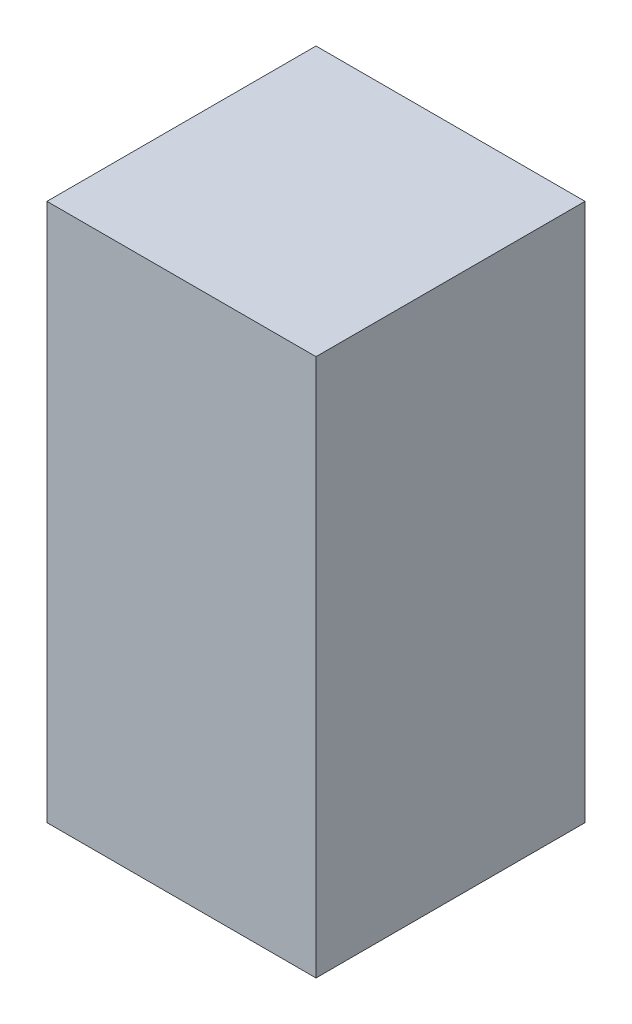
SolidWorks part; units mm, degrees
ref_plane "Front Plane" through (0, 0, 0) normal (0, 0, 1) x (1, 0, 0)
ref_plane "Top Plane" through (0, 0, 0) normal (0, 1, 0) x (1, 0, 0)
ref_plane "Right Plane" through (0, 0, 0) normal (1, 0, 0) x (0, 0, -1)
sketch "Sketch1" plane through (0, 0, 0) normal (0, 1, 0) x (1, 0, 0)
  line L1 (-150, -150) -> (150, -150)
  line L2 (-150, -150) -> (-150, 150)
  line L3 (-150, 150) -> (150, 150)
  line L4 (150, -150) -> (150, 150)
  line L5 (-150, -150) -> (150, 150) construction
  line L6 (-150, 150) -> (150, -150) construction
  point P0 (0, 0)
  dimension "D1" = 300
  dimension "D2" = 300
extrude "Boss-Extrude1" add sketch "Sketch1" along normal blind 600
sketch "Sketch2" plane through (0, 0, 0) normal (0, -1, 0) x (1, 0, 0)
  circle A0 centre (0, 0) radius 142.6011
  dimension "D1" = 285.2021
extrude "Cut-Extrude1" cut sketch "Sketch2" against normal blind 142.6
sketch "Sketch3" plane through (0, 142.6, 0) normal (0, -1, 0) x (1, 0, 0)
  line L0 (0, 142.6011) -> (0, -142.6011)
  arc A0 (0, 142.6011) -> (0, -142.6011) centre (0, 0) ccw
  dimension "D1" = 142.6011
revolve "Revolve1" add sketch "Sketch3" angle 180 about L0
